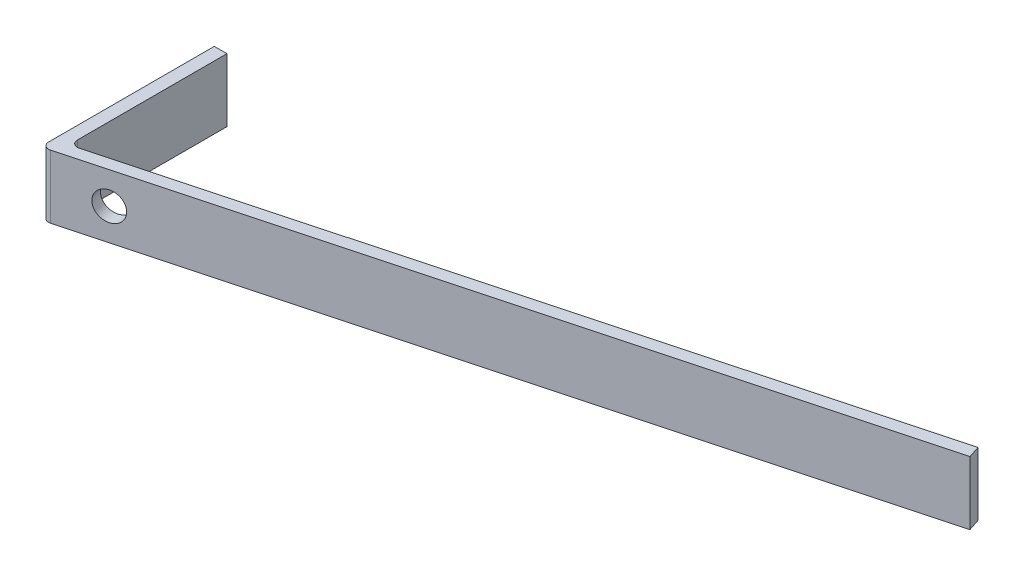
SolidWorks part; units mm, degrees
ref_plane "Front Plane" through (0, 0, 0) normal (0, 0, 1) x (1, 0, 0)
ref_plane "Top Plane" through (0, 0, 0) normal (0, 1, 0) x (1, 0, 0)
ref_plane "Right Plane" through (0, 0, 0) normal (1, 0, 0) x (0, 0, -1)
sketch "Sketch1" plane through (0, 0, 0) normal (0, 1, 0) x (1, 0, 0)
  line L0 (0, 0) -> (2, 0.5359)
  line L2 (0, 0) -> (0, 27.5)
  line L3 (0, 27.5) -> (2, 27.5)
  line L4 (2, 0.5359) -> (2, 27.5)
  dimension "D2" = 27.5
  dimension "D3" = 75
extrude "Boss-Extrude1" add sketch "Sketch1" along normal blind 10
sketch "Sketch3" plane through (0, 0, 0) normal (0, -1, 0) x (1, 0, 0)
  line L0 (0, 0) -> (115.9111, -31.0583)
  line L1 (0, 0) -> (0, -2)
  line L2 (0, -27.5) -> (0, 0) construction
  line L3 (0, -2) -> (115.2858, -32.958)
  line L4 (115.2858, -32.958) -> (115.9111, -31.0583)
  dimension "D1" = 75
  dimension "D2" = 2
  dimension "D3" = 2
extrude "Boss-Extrude2" add sketch "Sketch3" against normal blind 10
fillet "Fillet1" radius 1 2 edges at (0, 5, 0) (2, 5, -2.5371)
sketch "Sketch4" plane through (-0.5009, 0, -1.8655) normal (-0.2593, 0, -0.9658) x (-0.9658, 0, 0.2593)
  line L0 (-3.8935, 0) -> (-3.8935, 10) construction
  line L1 (-3.8935, 10) -> (-119.8888, 10) construction
  circle A0 centre (-8.8935, 5) radius 2.25
  dimension "D1" = 4.5
  dimension "D2" = 5
  dimension "D3" = 5
extrude "Cut-Extrude1" cut sketch "Sketch4" against normal blind 10
